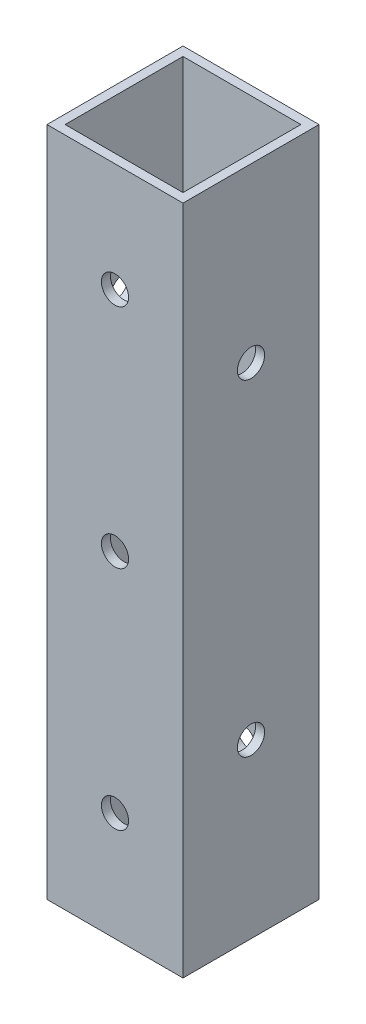
SolidWorks part; units mm, degrees
material "6063-T4"
ref_plane "前视基准面" through (0, 0, 0) normal (0, 0, 1) x (1, 0, 0)
ref_plane "上视基准面" through (0, 0, 0) normal (0, 1, 0) x (1, 0, 0)
ref_plane "右视基准面" through (0, 0, 0) normal (1, 0, 0) x (0, 0, -1)
sketch "草图1" plane through (0, 0, 0) normal (0, 1, 0) x (1, 0, 0)
  line B0 (-6.5, 6.5) -> (6.5, 6.5)
  line B1 (-7.5, -7.5) -> (7.5, -7.5)
  line B2 (-7.5, -7.5) -> (-7.5, 7.5)
  line B3 (-7.5, 7.5) -> (7.5, 7.5)
  line B4 (7.5, -7.5) -> (7.5, 7.5)
  line B5 (6.5, -6.5) -> (6.5, 6.5)
  line B6 (-6.5, -6.5) -> (6.5, -6.5)
  line B7 (-6.5, -6.5) -> (-6.5, 6.5)
sketch_block_instance "块-15X15X1-1"
sketch_block "块-15X15X1" parameters "D1"=15
extrude "凸台-拉伸1" add sketch "草图1" along normal blind 74
sketch "草图2" plane through (0, 0, 7.5) normal (0, 0, 1) x (1, 0, 0)
  line L0 (0, 74) -> (0, -0.6907) construction
  line L1 (-7.5, 74) -> (7.5, 74) construction
  line L2 (-7.5, 37) -> (7.5, 37) construction
  line L3 (-7.5, 74) -> (-7.5, 0) construction
  line L4 (7.5, 74) -> (7.5, 0) construction
  circle A0 centre (0, 62) radius 1.5
  circle A1 centre (0, 37) radius 1.5
  circle A2 centre (0, 12) radius 1.5
  circle A4 centre (0, -13) radius 1.5 [skipped]
  dimension "D1" = 3
  dimension "D3" = 25
  dimension "D2" = 4
extrude "切除-拉伸1" cut sketch "草图2" against normal through all
sketch "草图3" plane through (7.5, 0, 0) normal (1, 0, 0) x (0, 0, -1)
  line L0 (0, 74) -> (0, 0) construction
  line L1 (-7.5, 74) -> (7.5, 74) construction
  line L2 (-7.5, 37) -> (7.5, 37) construction
  line L3 (-7.5, 74) -> (-7.5, 0) construction
  line L4 (7.5, 74) -> (7.5, 0) construction
  circle A1 centre (0, 55) radius 1.5
  circle A2 centre (0, 19) radius 1.5
  dimension "D1" = 36
  dimension "D2" = 3
extrude "切除-拉伸2" cut sketch "草图3" against normal through all
